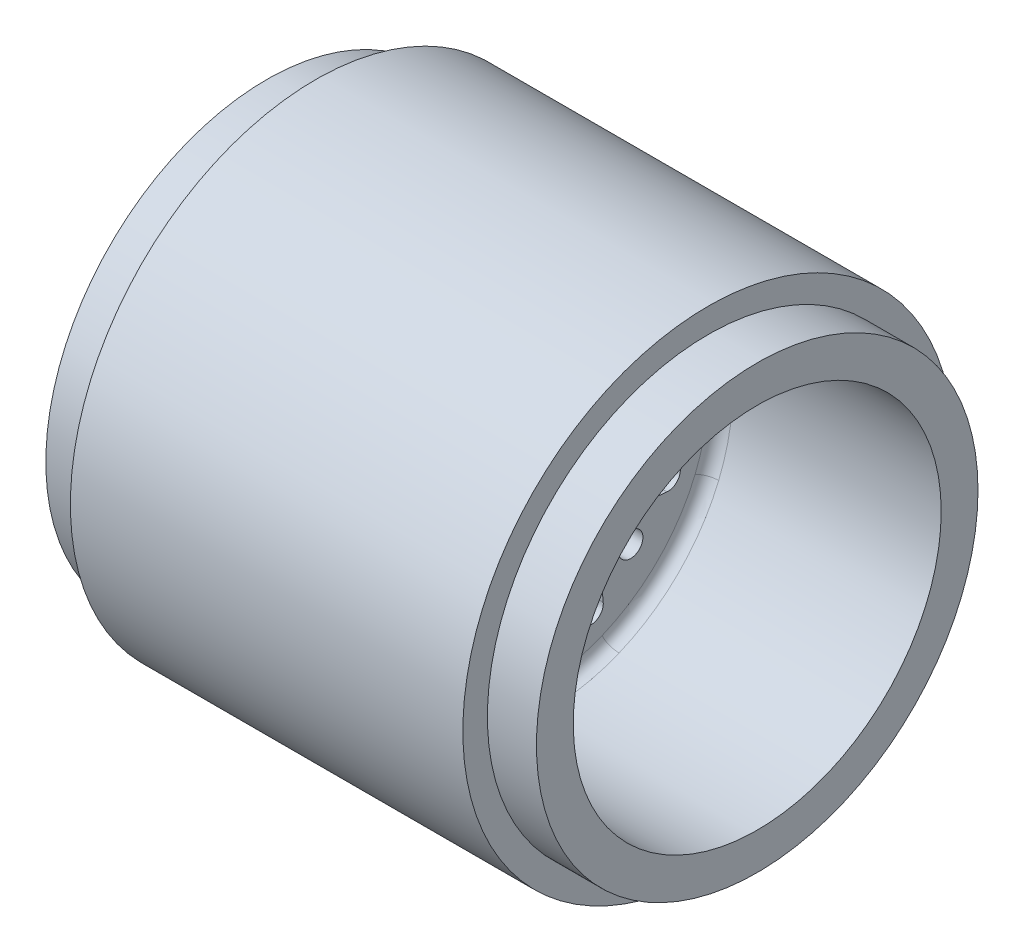
SolidWorks part; units mm, degrees
material "Nailon 101"
ref_plane "Alzado" through (0, 0, 0) normal (0, 0, 1) x (1, 0, 0)
ref_plane "Planta" through (0, 0, 0) normal (0, 1, 0) x (1, 0, 0)
ref_plane "Vista lateral" through (0, 0, 0) normal (1, 0, 0) x (0, 0, -1)
sketch "Croquis1" plane through (0, 0, 0) normal (1, 0, 0) x (0, 0, -1)
  circle A0 centre (0, 0) radius 100
  dimension "D1" = 200
extrude "Saliente-Extruir1" add sketch "Croquis1" along normal mid plane 200
shell "Vaciado1" thickness 25
sketch "Croquis2" plane through (0, 0, 0) normal (1, 0, 0) x (0, 0, -1)
  line L0 (-69.291, -13.6183) -> (-69.291, -28.7013) construction
  line L1 (0.0681, 75) -> (-13.7147, 69.291) construction
  line L2 (-52.9649, 53.033) -> (-58.6257, 39.3665) construction
  line L3 (-74.9319, 0) -> (-69.291, -13.6183) construction
  line L4 (-52.9649, -53.033) -> (-39.2984, -58.6939) construction
  line L5 (0.0681, -75) -> (13.851, -69.291) construction
  line L6 (53.1011, -53.033) -> (58.8584, -39.1339) construction
  line L7 (75.0681, 0) -> (69.291, 13.9473) construction
  line L8 (53.1011, 53.033) -> (39.202, 58.7902) construction
  line L9 (-69.291, 28.7013) -> (-69.291, 13.6183) construction
  line L10 (-69.291, -28.7013) -> (-58.6257, -39.3665) construction
  line L11 (-28.7013, -69.291) -> (-13.7147, -69.291) construction
  line L12 (28.7013, -69.291) -> (39.202, -58.7902) construction
  line L13 (69.291, -28.7013) -> (69.291, -13.9473) construction
  line L14 (69.291, 28.7013) -> (58.8584, 39.1339) construction
  line L15 (28.7013, 69.291) -> (13.851, 69.291) construction
  line L16 (-28.7013, 69.291) -> (-39.2984, 58.6939) construction
  line L17 (-69.291, 13.6183) -> (-74.9319, 0) construction
  line L18 (-58.6257, 39.3665) -> (-69.291, 28.7013) construction
  line L19 (-39.2984, 58.6939) -> (-52.9649, 53.033) construction
  line L20 (-13.7147, 69.291) -> (-28.7013, 69.291) construction
  line L21 (13.851, 69.291) -> (0.0681, 75) construction
  line L22 (39.202, 58.7902) -> (28.7013, 69.291) construction
  line L23 (58.8584, 39.1339) -> (53.1011, 53.033) construction
  line L24 (69.291, 13.9473) -> (69.291, 28.7013) construction
  line L25 (69.291, -13.9473) -> (75.0681, 0) construction
  line L26 (58.8584, -39.1339) -> (69.291, -28.7013) construction
  line L27 (-58.6257, -39.3665) -> (-52.9649, -53.033) construction
  line L28 (-39.2984, -58.6939) -> (-28.7013, -69.291) construction
  line L29 (-13.7147, -69.291) -> (0.0681, -75) construction
  line L30 (13.851, -69.291) -> (28.7013, -69.291) construction
  line L31 (39.202, -58.7902) -> (53.1011, -53.033) construction
  line L32 (0.0681, 75) -> (0.0681, -75) construction
  line L33 (-74.9319, 0) -> (75.0681, 0) construction
  line L34 (53.1011, 53.033) -> (-52.9649, -53.033) construction
  line L35 (53.1011, -53.033) -> (-52.9649, 53.033) construction
  line L36 (-28.7013, -69.291) -> (28.7013, 69.291) construction
  line L37 (-28.7013, 69.291) -> (28.7013, -69.291) construction
  line L38 (-69.291, 28.7013) -> (69.291, -28.7013) construction
  line L39 (-69.291, -28.7013) -> (69.291, 28.7013) construction
  line L40 (-13.7147, -69.291) -> (13.851, 69.291) construction
  line L41 (13.851, -69.291) -> (-13.7147, 69.291) construction
  line L42 (39.202, -58.7902) -> (-39.2984, 58.6939) construction
  line L43 (58.8584, -39.1339) -> (-58.6257, 39.3665) construction
  line L44 (69.291, -13.9473) -> (-69.291, 13.6183) construction
  line L45 (69.291, 13.9473) -> (-69.291, -13.6183) construction
  line L46 (58.8584, 39.1339) -> (-58.6257, -39.3665) construction
  line L47 (-39.2984, -58.6939) -> (39.202, 58.7902) construction
  line L48 (-28.7013, -69.291) -> (-9.0076, -45.6267)
  line L49 (9.1439, -45.6267) -> (28.7013, -69.291)
  line L50 (-69.291, -28.7013) -> (-38.6323, -25.8936)
  line L51 (-25.7973, -38.7286) -> (-28.7013, -69.291)
  line L52 (-69.291, 28.7013) -> (-45.6267, 9.0076)
  line L53 (-45.6267, -9.1439) -> (-69.291, -28.7013)
  line L54 (-28.7013, 69.291) -> (-25.8936, 38.6323)
  line L55 (-38.7286, 25.7973) -> (-69.291, 28.7013)
  line L56 (28.7013, 69.291) -> (9.0076, 45.6267)
  line L57 (-9.1439, 45.6267) -> (-28.7013, 69.291)
  line L58 (69.291, 28.7013) -> (38.6323, 25.8936)
  line L59 (25.7973, 38.7286) -> (28.7013, 69.291)
  line L60 (69.291, -28.7013) -> (45.6267, -9.0076)
  line L61 (45.6267, 9.1439) -> (69.291, 28.7013)
  line L62 (28.7013, -69.291) -> (25.8936, -38.6323)
  line L63 (38.7286, -25.7973) -> (69.291, -28.7013)
  circle A1 centre (0.0681, -54.2367) radius 5
  circle A2 centre (0, 0) radius 75 construction
  arc A4 (-9.0076, -45.6267) -> (9.1439, -45.6267) centre (0.0681, -54.2367) cw
  arc A5 (-28.7013, -69.291) -> (28.7013, -69.291) centre (0, 0) ccw
  arc A6 (-69.291, -28.7013) -> (-28.7013, -69.291) centre (0, 0) ccw
  arc A7 (-38.6323, -25.8936) -> (-25.7973, -38.7286) centre (-38.3029, -38.3993) cw
  circle A8 centre (-38.3029, -38.3993) radius 5
  arc A9 (-69.291, 28.7013) -> (-69.291, -28.7013) centre (0, 0) ccw
  arc A10 (-45.6267, 9.0076) -> (-45.6267, -9.1439) centre (-54.2367, -0.0681) cw
  circle A11 centre (-54.2367, -0.0681) radius 5
  arc A12 (-28.7013, 69.291) -> (-69.291, 28.7013) centre (0, 0) ccw
  arc A13 (-25.8936, 38.6323) -> (-38.7286, 25.7973) centre (-38.3993, 38.3029) cw
  circle A14 centre (-38.3993, 38.3029) radius 5
  arc A15 (28.7013, 69.291) -> (-28.7013, 69.291) centre (0, 0) ccw
  arc A16 (9.0076, 45.6267) -> (-9.1439, 45.6267) centre (-0.0681, 54.2367) cw
  circle A17 centre (-0.0681, 54.2367) radius 5
  arc A18 (69.291, 28.7013) -> (28.7013, 69.291) centre (0, 0) ccw
  arc A19 (38.6323, 25.8936) -> (25.7973, 38.7286) centre (38.3029, 38.3993) cw
  circle A20 centre (38.3029, 38.3993) radius 5
  arc A21 (69.291, -28.7013) -> (69.291, 28.7013) centre (0, 0) ccw
  arc A22 (45.6267, -9.0076) -> (45.6267, 9.1439) centre (54.2367, 0.0681) cw
  circle A23 centre (54.2367, 0.0681) radius 5
  arc A24 (28.7013, -69.291) -> (69.291, -28.7013) centre (0, 0) ccw
  arc A25 (25.8936, -38.6323) -> (38.7286, -25.7973) centre (38.3993, -38.3029) cw
  circle A26 centre (38.3993, -38.3029) radius 5
  point P92 (0, 0)
  dimension "D1" = 10
  dimension "D2" = 12.51
  dimension "D3" = 30.7
  dimension "D4" = 8
extrude "Saliente-Extruir3" add sketch "Croquis2" along normal mid plane 20 contours L54 A13 L55 A12 | L56 A16 L57 A15 | L58 A19 L59 A18 | L60 A22 L61 A21 | L62 A25 L63 A24 | A5 L49 A4 L48 | L50 A7 L51 A6 | L52 A10 L53 A9 | A11 | A14 | A17 | A20 | A23 | A26 | A1 | A8
fillet "Redondeo1" radius 5 8 edges at (0, -28.7013, 69.291) (0, 28.7013, 69.291) (0, -69.291, 28.7013) (0, -69.291, -28.7013) (0, -28.7013, -69.291) (0, 28.7013, -69.291) (0, 69.291, -28.7013) (0, 69.291, 28.7013)
fillet "Redondeo2" radius 5 16 edges at (10, 53.033, 53.033) (10, 75, 0) (10, 53.033, -53.033) (10, 0, -75) (10, -53.033, -53.033) (10, -75, 0) (10, -53.033, 53.033) (10, 0, 75) (-10, 75, 0) (-10, 53.033, 53.033) (-10, 0, 75) (-10, -53.033, 53.033) (-10, -75, 0) (-10, -53.033, -53.033) (-10, 0, -75) (-10, 53.033, -53.033)
sketch "Croquis4" plane through (100, 0, 0) normal (1, 0, 0) x (0, 0, -1)
  circle A0 centre (0, 0) radius 100
  circle A1 centre (0, 0) radius 90
  dimension "D1" = 180
extrude "Cortar-Extruir1" cut sketch "Croquis4" against normal blind 20 contours A0 | A1
mirror "Simetría1" about plane through (0, 0, 0) normal (1, 0, 0) of "Cortar-Extruir1"
ref_plane "Plano1" through (0, 0, 100) normal (0, 0, 1) x (1, 0, 0)
ref_plane "Plano2" through (-200, 0, 0) normal (-1, 0, 0) x (0, 0, 1)
